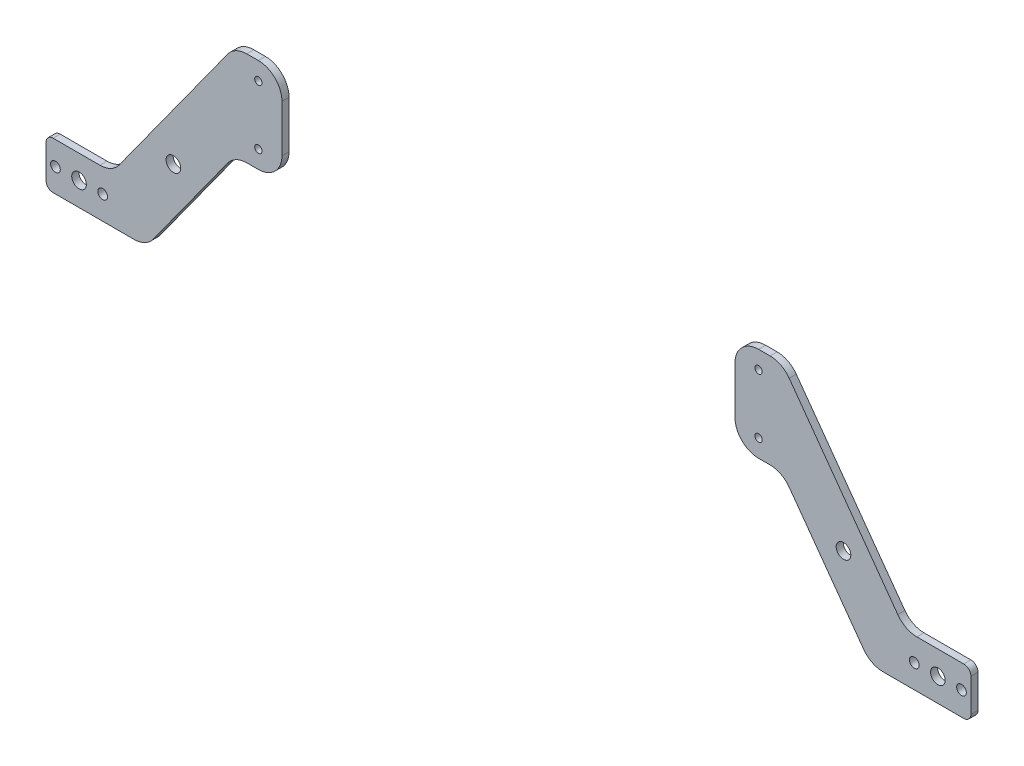
SolidWorks part; units mm, degrees
material "Thornel Mat VMA"
ref_plane "前视基准面" through (0, 0, 0) normal (0, 0, 1) x (1, 0, 0)
ref_plane "上视基准面" through (0, 0, 0) normal (0, 1, 0) x (1, 0, 0)
ref_plane "右视基准面" through (0, 0, 0) normal (1, 0, 0) x (0, 0, -1)
other "Configuration Table"
sketch "草图1" plane through (0, 0, 0) normal (0, 0, 1) x (1, 0, 0)
  line L1 (-47.5, -12.5) -> (47.5, -12.5) construction
  line L2 (-47.5, -12.5) -> (-47.5, 12.5) construction
  line L3 (-47.5, 12.5) -> (47.5, 12.5) construction
  line L4 (47.5, -12.5) -> (47.5, 12.5) construction
  line L5 (-47.5, -12.5) -> (47.5, 12.5) construction
  line L6 (-47.5, 12.5) -> (47.5, -12.5) construction
  line L7 (-116, -20) -> (116, -20)
  line L8 (-116, -20) -> (-116, 20)
  line L9 (-116, 20) -> (116, 20)
  line L10 (116, -20) -> (116, 20)
  line L11 (-116, -20) -> (116, 20) construction
  line L12 (-116, 20) -> (116, -20) construction
  circle A0 centre (-47.5, 12.5) radius 2.1
  circle A1 centre (47.5, 12.5) radius 2.1
  circle A2 centre (-47.5, -12.5) radius 2.1
  circle A3 centre (47.5, -12.5) radius 2.1
  point P0 (0, 0)
  point P10 (0, 0)
  dimension "D1" = 4.2
  dimension "D2" = 95
  dimension "D3" = 25
  dimension "D4" = 40
  dimension "D5" = 232
extrude "凸台-拉伸1" add sketch "草图1" along normal blind 3
sketch "草图2" plane through (0, 0, 3) normal (0, 0, 1) x (1, 0, 0)
  line L0 (-116, 20) -> (-168, -52)
  line L1 (-168, -52) -> (-196, -52)
  line L2 (-196, -52) -> (-196, -72)
  line L3 (-196, -72) -> (-153.5556, -72)
  line L4 (-153.5556, -72) -> (-116, -20)
  line L5 (-116, 20) -> (-116, -20)
  line L6 (0, -1000) -> (0, 49000) construction
  line L7 (116, 20) -> (168, -52)
  line L8 (168, -52) -> (196, -52)
  line L9 (196, -52) -> (196, -72)
  line L10 (196, -72) -> (153.5556, -72)
  line L11 (153.5556, -72) -> (116, -20)
  line L12 (116, 20) -> (116, -20)
  line L13 (-116, 0) -> (-168, -72) construction
  circle A0 centre (-142, -36) radius 3.1
  circle A1 centre (142, -36) radius 3.1
  dimension "D5" = 6.2
  dimension "D1" = 52
  dimension "D2" = 72
  dimension "D3" = 20
  dimension "D4" = 28
extrude "凸台-拉伸2" add sketch "草图2" against normal up to surface (3 mm away) up to face at (-45.4, -12.5, 0)
sketch "草图4" plane through (0, 0, 3) normal (0, 0, 1) x (1, 0, 0)
  line L0 (0, 0) -> (50000, 0) construction
  line L1 (-116, -20) -> (116, -20) construction
  line L2 (-116, 20) -> (-96, 20) construction
  line L3 (-116, 20) -> (-116, -20) construction
  line L4 (-116, -20) -> (-96, -20) construction
  line L5 (-96, 20) -> (-96, -20) construction
  line L6 (-116, 20) -> (-96, -20) construction
  line L7 (116, 20) -> (96, 20) construction
  line L8 (116, 20) -> (116, -20) construction
  line L9 (116, -20) -> (96, -20) construction
  line L10 (96, 20) -> (96, -20) construction
  line L11 (96, -20) -> (116, 20) construction
  line L12 (-106, 20) -> (-106, -20) construction
  line L13 (106, 20) -> (106, -20) construction
  line L14 (-106, 12.5) -> (-47.5, 12.5) construction
  line L15 (-106, 12.5) -> (106, 12.5) construction
  line L16 (-106, 12.5) -> (-106, -12.5) construction
  line L17 (-106, -12.5) -> (106, -12.5) construction
  line L18 (106, 12.5) -> (106, -12.5) construction
  line L19 (-106, -12.5) -> (-47.5, -12.5) construction
  circle A1 centre (-106, 12.5) radius 1.55
  circle A2 centre (-106, -12.5) radius 1.55
  circle A3 centre (106, 12.5) radius 1.55
  circle A4 centre (106, -12.5) radius 1.55
  dimension "D2" = 3.1
  dimension "D1" = 20
extrude "切除-拉伸2" cut sketch "草图4" against normal blind 10
fillet "圆角1" radius 3 4 edges at (196, -72, 1.5) (196, -52, 1.5) (-196, -52, 1.5) (-196, -72, 1.5)
fillet "圆角2" radius 10 8 edges at (168, -52, 1.5) (116, 20, 1.5) (-116, 20, 1.5) (-168, -52, 1.5) (-153.5556, -72, 1.5) (-116, -20, 1.5) (116, -20, 1.5) (153.5556, -72, 1.5)
sketch "草图5" plane through (0, 0, 3) normal (0, 0, 1) x (1, 0, 0)
  line L0 (-106, 12.5) -> (-106, -12.5) construction
  line L1 (110.8869, 20) -> (-110.8869, 20) construction
  line L2 (-116, -20) -> (-96, -20) construction
  line L3 (-116, -20) -> (-116, 20) construction
  line L4 (-116, 20) -> (-96, 20) construction
  line L5 (-96, -20) -> (-96, 20) construction
  line L6 (-116, -20) -> (-96, 20) construction
  line L7 (-116, 20) -> (-96, -20) construction
  line L8 (-110.8869, -20) -> (110.8869, -20) construction
  line L9 (106, 12.5) -> (106, -12.5) construction
  line L10 (-96, 20) -> (96, 20)
  line L11 (-96, 20) -> (-96, -20)
  line L12 (-96, -20) -> (96, -20)
  line L13 (96, 20) -> (96, -20)
  line L14 (96, 20) -> (116, 20) construction
  line L15 (96, 20) -> (96, -20) construction
  line L16 (96, -20) -> (116, -20) construction
  line L17 (116, 20) -> (116, -20) construction
  point P2 (-106, 0)
  dimension "D1" = 20
  dimension "D2" = 20
  dimension "D3" = 10
extrude "切除-拉伸3" cut sketch "草图5" against normal mid plane 10
fillet "圆角3" radius 10 2 edges at (-96, 20, 1.5) (-96, -20, 1.5)
fillet "圆角4" radius 10 2 edges at (96, -20, 1.5) (96, 20, 1.5)
sketch "草图6" plane through (0, 0, 3) normal (0, 0, 1) x (1, 0, 0)
  line L0 (-191, -62) -> (49809, -62) construction
  line L1 (-196, -55) -> (-196, -69) construction
  line L2 (0, 0) -> (0, -50000) construction
  line L3 (-192, -62) -> (-172, -62) construction
  line L4 (-192, -62) -> (-172, -62) construction
  circle A0 centre (-192, -62) radius 2.05
  circle A1 centre (-172, -62) radius 2.05
  circle A6 centre (172, -62) radius 2.05
  circle A7 centre (192, -62) radius 2.05
  circle A8 centre (-182, -62) radius 3.1
  circle A9 centre (182, -62) radius 3.1
  point P4 (-196, -62)
  point P12 (182, -62)
  dimension "D1" = 4
  dimension "D2" = 20
  dimension "D3" = 6.2
  dimension "D5" = 4.1
  dimension "D4" = 10
  dimension "D6" = 6.2
  dimension "D7" = 10
extrude "切除-拉伸4" cut sketch "草图6" against normal through all
